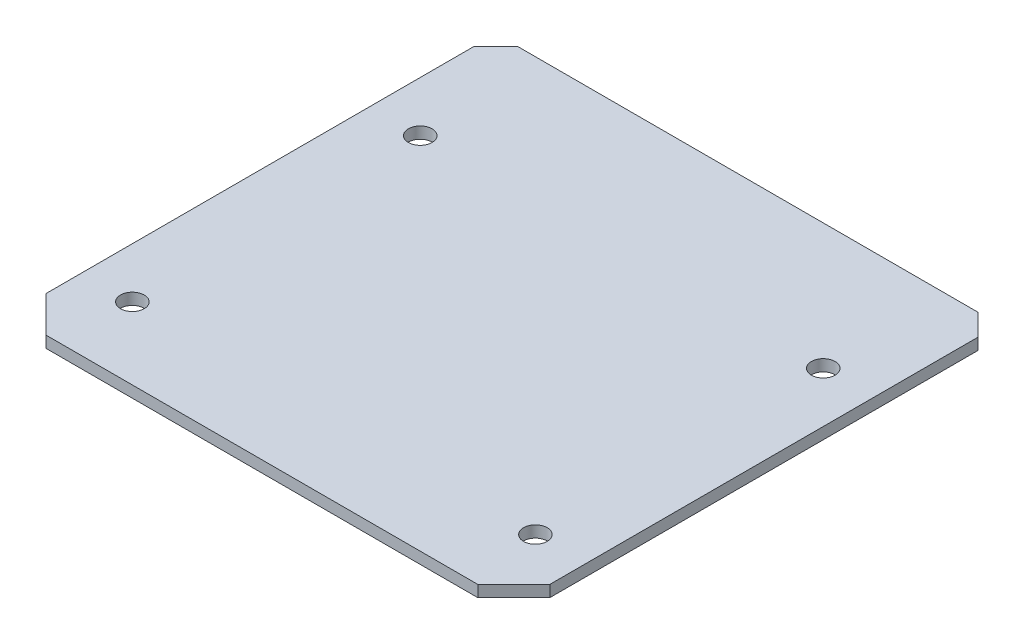
SolidWorks part; units mm, degrees
ref_plane "前视基准面" through (0, 0, 0) normal (0, 0, 1) x (1, 0, 0)
ref_plane "上视基准面" through (0, 0, 0) normal (0, 1, 0) x (1, 0, 0)
ref_plane "右视基准面" through (0, 0, 0) normal (1, 0, 0) x (0, 0, -1)
sketch "草图1" plane through (0, 0, 0) normal (0, 1, 0) x (1, 0, 0)
  line L1 (-35, -25) -> (35, -25)
  line L2 (-35, -25) -> (-35, 25)
  line L3 (-35, 25) -> (35, 25)
  line L4 (35, -25) -> (35, 25)
  line L5 (-35, -25) -> (35, 25) construction
  line L6 (-35, 25) -> (35, -25) construction
  point P0 (0, 0)
  dimension "D1" = 50
  dimension "D2" = 70
extrude "凸台-拉伸1" add sketch "草图1" along normal blind 1.6
sketch "草图2" plane through (0, 1.6, 0) normal (0, 1, 0) x (1, 0, 0)
  line L1 (-28, -20) -> (28, -20) construction
  line L2 (-28, -20) -> (-28, 20) construction
  line L3 (-28, 20) -> (28, 20) construction
  line L4 (28, -20) -> (28, 20) construction
  line L5 (-28, -20) -> (28, 20) construction
  line L6 (-28, 20) -> (28, -20) construction
  circle A0 centre (-28, 20) radius 1.65
  circle A1 centre (-28, -20) radius 1.65
  circle A2 centre (28, -20) radius 1.65
  circle A3 centre (28, 20) radius 1.65
  point P0 (0, 0)
  dimension "D3" = 3.3
  dimension "D1" = 56
  dimension "D2" = 40
extrude "切除-拉伸1" cut sketch "草图2" against normal up to next
sketch "草图3" plane through (0, 0, 0) normal (0, 1, 0) x (1, 0, 0)
  line L0 (-35, -25) -> (-30, -30)
  line L1 (-30, -30) -> (30, -30)
  line L2 (30, -30) -> (35, -25)
  line L3 (35, -25) -> (-35, -25)
  line L4 (35, -25) -> (35, 25) construction
  line L5 (-35, 25) -> (35, 25)
  line L6 (-35, 25) -> (-35, 37.5)
  line L7 (-35, 37.5) -> (35, 37.5)
  line L8 (35, 25) -> (35, 37.5)
  dimension "D1" = 45
  dimension "D2" = 45
  dimension "D3" = 5
  dimension "D4" = 12.5
extrude "凸台-拉伸2" add sketch "草图3" along normal up to surface (1.6 mm away) up to face at (28, 1.6, -18.35)
chamfer "倒角1" distance 3 angle 45 2 edges at (35, 0.8, -37.5) (-35, 0.8, -37.5)
